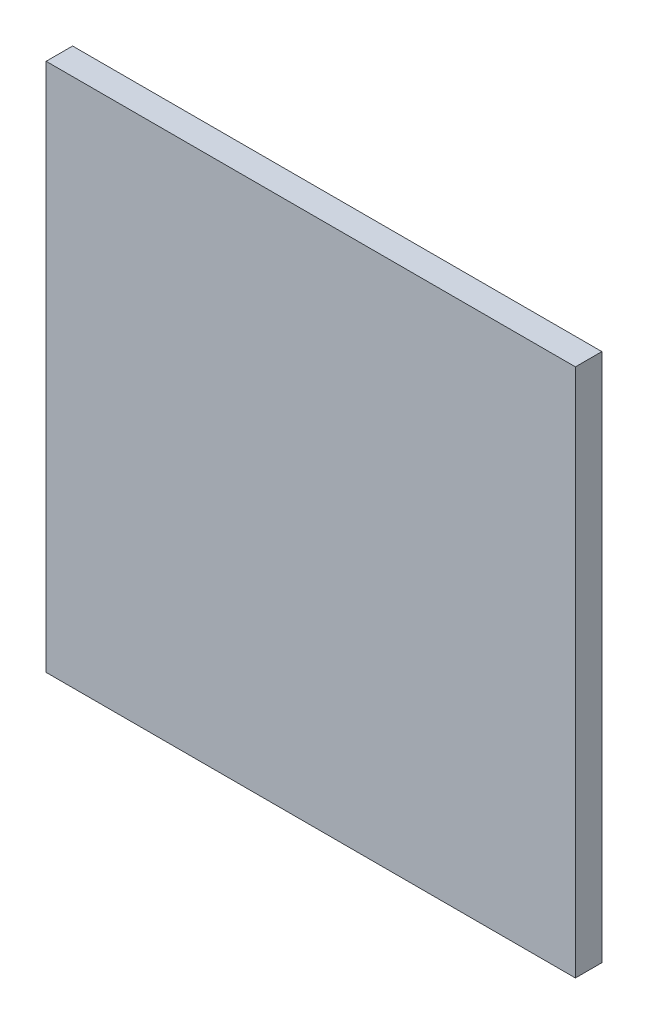
SolidWorks part; units mm, degrees
ref_plane "Front Plane" through (0, 0, 0) normal (0, 0, 1) x (1, 0, 0)
ref_plane "Top Plane" through (0, 0, 0) normal (0, 1, 0) x (1, 0, 0)
ref_plane "Right Plane" through (0, 0, 0) normal (1, 0, 0) x (0, 0, -1)
sketch "Sketch1" plane through (0, 0, 0) normal (0, 0, 1) x (1, 0, 0)
  line L1 (-50, -50) -> (50, -50)
  line L2 (-50, -50) -> (-50, 50)
  line L3 (-50, 50) -> (50, 50)
  line L4 (50, -50) -> (50, 50)
  line L5 (-50, -50) -> (50, 50) construction
  line L6 (-50, 50) -> (50, -50) construction
  point P0 (0, 0)
  dimension "D1" = 100
  dimension "D2" = 100
extrude "Boss-Extrude1" add sketch "Sketch1" along normal blind 5
